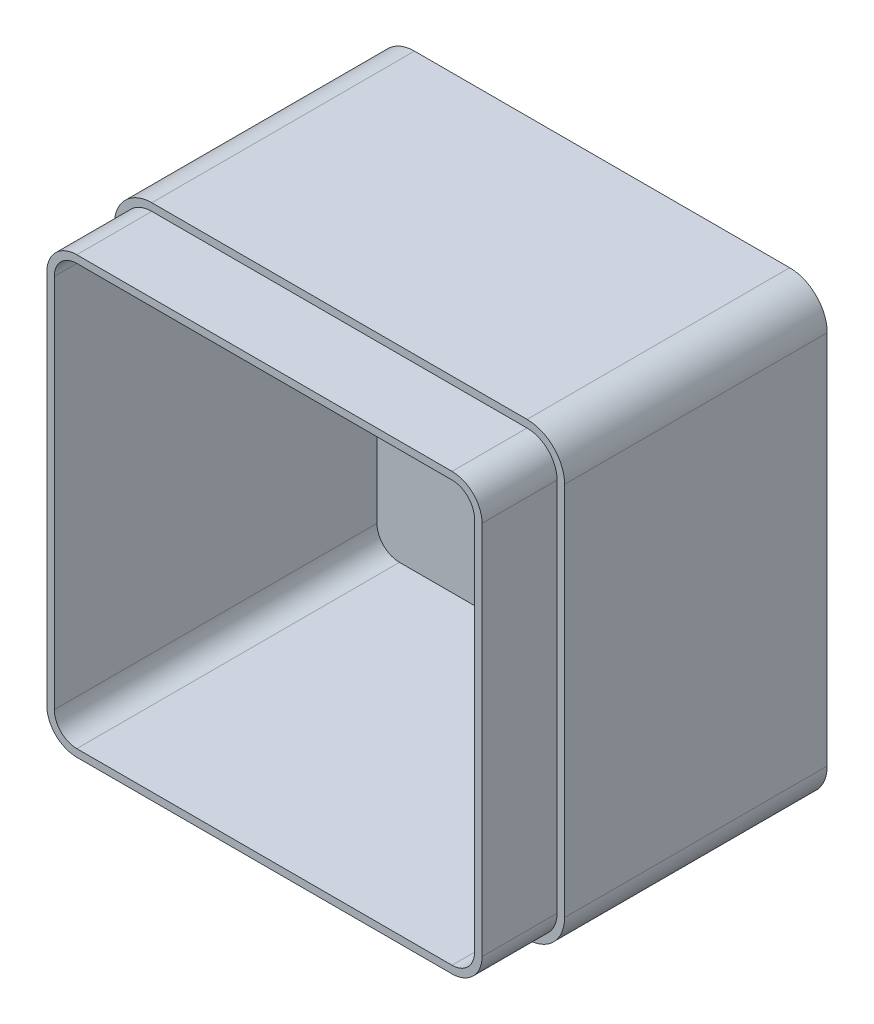
SolidWorks part; units mm, degrees
ref_plane "Front Plane" through (0, 0, 0) normal (0, 0, 1) x (1, 0, 0)
ref_plane "Top Plane" through (0, 0, 0) normal (0, 1, 0) x (1, 0, 0)
ref_plane "Right Plane" through (0, 0, 0) normal (1, 0, 0) x (0, 0, -1)
sketch "Sketch1" plane through (0, 0, 0) normal (0, 0, 1) x (1, 0, 0)
  line L1 (0, 0) -> (120, 0)
  line L2 (0, 0) -> (0, -120)
  line L3 (0, -120) -> (120, -120)
  line L4 (120, 0) -> (120, -120)
  dimension "D1" = 120
  dimension "D2" = 120
extrude "Boss-Extrude1" add sketch "Sketch1" along normal blind 90
fillet "Fillet1" radius 10 4 edges at (0, -120, 45) (120, -120, 45) (0, 0, 45) (120, 0, 45)
shell "Shell1" thickness 4
sketch "Sketch4" plane through (0, 0, 90) normal (0, 0, 1) x (1, 0, 0)
  line L0 (2, -10) -> (2, -110)
  line L1 (10, -118) -> (110, -118)
  line L2 (118, -110) -> (118, -10)
  line L3 (110, -2) -> (10, -2)
  line L4 (0, -10) -> (0, -110)
  line L5 (10, -120) -> (110, -120)
  line L6 (120, -110) -> (120, -10)
  line L7 (110, 0) -> (10, 0)
  line L8 (0, -10) -> (0, -110)
  line L9 (10, -120) -> (110, -120)
  line L10 (120, -110) -> (120, -10)
  line L11 (110, 0) -> (10, 0)
  arc A0 (2, -110) -> (10, -118) centre (10, -110) ccw
  arc A1 (110, -118) -> (118, -110) centre (110, -110) ccw
  arc A2 (118, -10) -> (110, -2) centre (110, -10) ccw
  arc A3 (10, -2) -> (2, -10) centre (10, -10) ccw
  arc A4 (0, -110) -> (10, -120) centre (10, -110) ccw
  arc A5 (110, -120) -> (120, -110) centre (110, -110) ccw
  arc A6 (120, -10) -> (110, 0) centre (110, -10) ccw
  arc A7 (10, 0) -> (0, -10) centre (10, -10) ccw
  arc A8 (0, -110) -> (10, -120) centre (10, -110) ccw
  arc A9 (110, -120) -> (120, -110) centre (110, -110) ccw
  arc A10 (120, -10) -> (110, 0) centre (110, -10) ccw
  arc A11 (10, 0) -> (0, -10) centre (10, -10) ccw
  dimension "D1" = 0
  dimension "D2" = 2
extrude "Cut-Extrude5" cut sketch "Sketch4" against normal blind 20 contours L8 A8 L9 A9 L10 A10 L11 A11 | L0 A0 L1 A1 L2 A2 L3 A3
